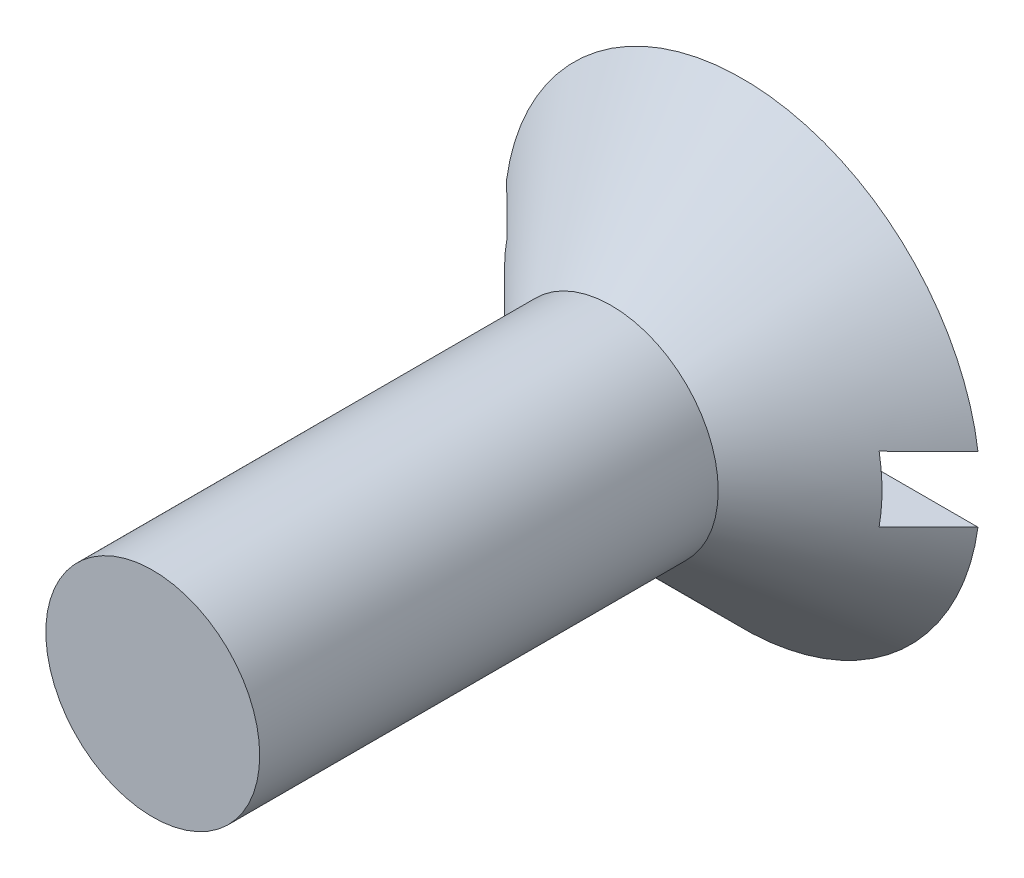
SolidWorks part; units mm, degrees
ref_plane "Plano frontal" through (0, 0, 0) normal (0, 0, 1) x (1, 0, 0)
ref_plane "Plano superior" through (0, 0, 0) normal (0, 1, 0) x (1, 0, 0)
ref_plane "Plano direito" through (0, 0, 0) normal (1, 0, 0) x (0, 0, -1)
sketch "Esboço1" plane through (0, 0, 0) normal (1, 0, 0) x (0, 0, -1)
  line L0 (0, 0) -> (0, 7.265)
  line L1 (0, 7.265) -> (-4, 3.265)
  line L2 (-4, 3.265) -> (-18, 3.265)
  line L3 (-18, 3.265) -> (-18, 0)
  line L4 (-18, 0) -> (0, 0) construction
  line L5 (0, 0) -> (-18, 0)
  dimension "D1" = 7.265
  dimension "D2" = 14
  dimension "D3" = 4
  dimension "D4" = 3.265
revolve "Revolução1" add sketch "Esboço1" angle 360 about L4
sketch "Esboço2" plane through (0, 0, 0) normal (0, 0, -1) x (-1, 0, 0)
  line L1 (-7.5, -1) -> (7.5, -1)
  line L2 (-7.5, -1) -> (-7.5, 1)
  line L3 (-7.5, 1) -> (7.5, 1)
  line L4 (7.5, -1) -> (7.5, 1)
  line L5 (-7.5, -1) -> (7.5, 1) construction
  line L6 (-7.5, 1) -> (7.5, -1) construction
  point P0 (0, 0)
  dimension "D1" = 15
  dimension "D2" = 2
extrude "Corte-extrusão1" cut sketch "Esboço2" against normal blind 1.5
